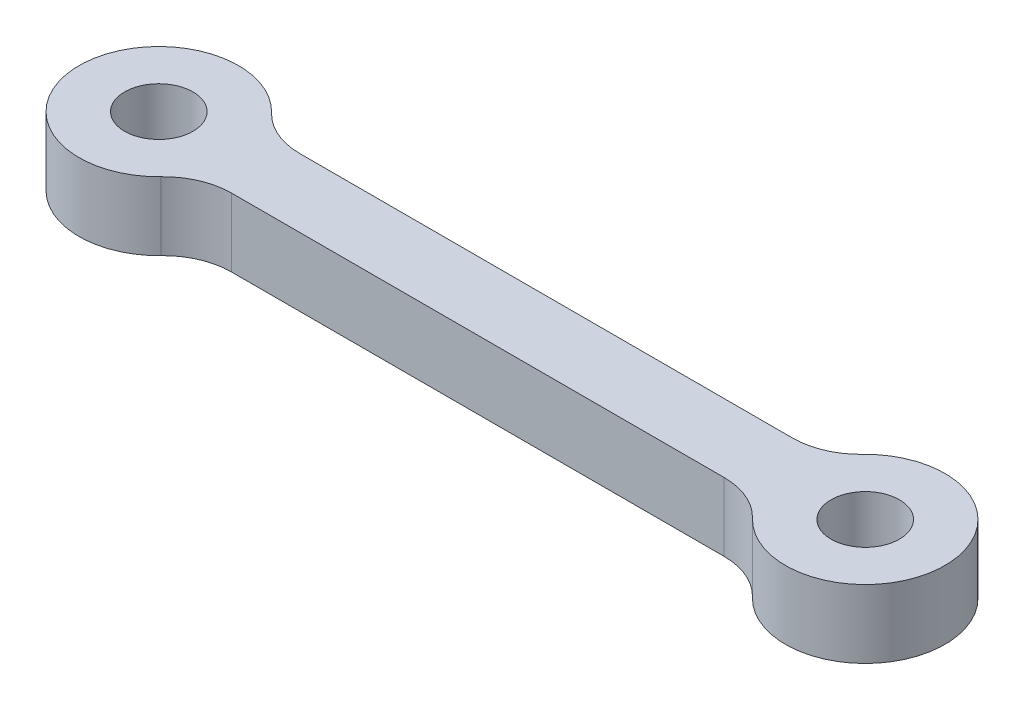
SolidWorks part; units mm, degrees
ref_plane "Front Plane" through (0, 0, 0) normal (0, 0, 1) x (1, 0, 0)
ref_plane "Top Plane" through (0, 0, 0) normal (0, 1, 0) x (1, 0, 0)
ref_plane "Right Plane" through (0, 0, 0) normal (1, 0, 0) x (0, 0, -1)
sketch "Sketch1" plane through (0, 0, 0) normal (0, 1, 0) x (1, 0, 0)
  line L0 (0, 0) -> (31, 0) construction
  line L1 (3.1623, 1.5) -> (27.8377, 1.5)
  line L2 (3.1623, -1.5) -> (27.8377, -1.5)
  circle A0 centre (0, 0) radius 3.5
  circle A1 centre (31, 0) radius 3.5
  circle A2 centre (0, 0) radius 1.5
  circle A3 centre (31, 0) radius 1.5
  dimension "D1" = 7
  dimension "D3" = 7
  dimension "D5" = 3
  dimension "D6" = 3
  dimension "D2" = 31
  dimension "D4" = 1.5
extrude "Boss-Extrude1" add sketch "Sketch1" along normal blind 3
fillet "Fillet1" radius 3 4 edges at (3.1623, 1.5, 1.5) (27.8377, 1.5, 1.5) (27.8377, 1.5, -1.5) (3.1623, 1.5, -1.5)
scale "Scale1" scale about centroid uniform scaling yes scale factor 0.888889
